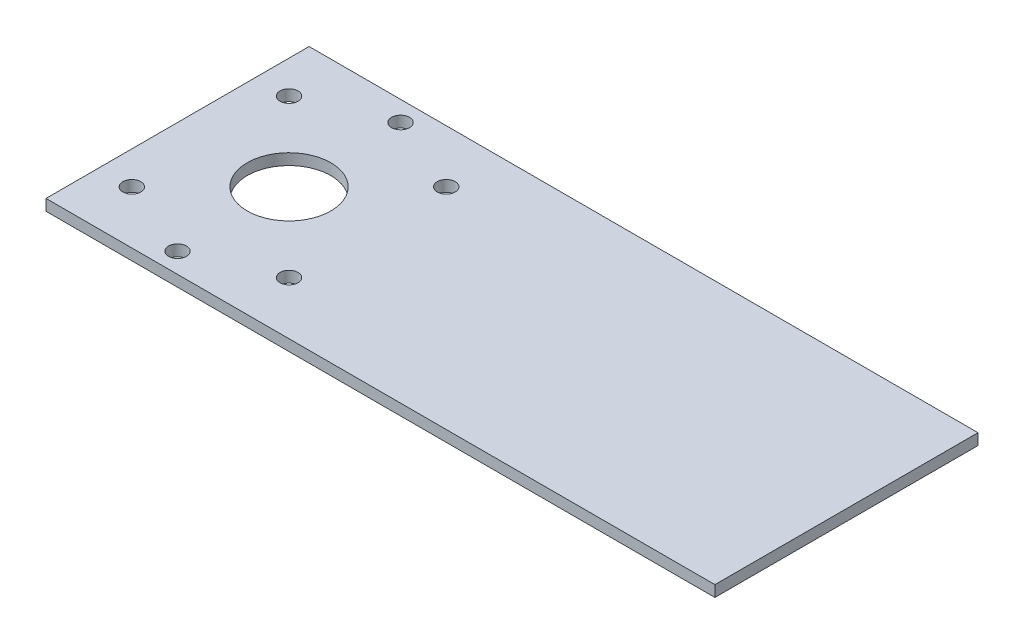
SolidWorks part; units mm, degrees
ref_plane "Front Plane" through (0, 0, 0) normal (0, 0, 1) x (1, 0, 0)
ref_plane "Top Plane" through (0, 0, 0) normal (0, 1, 0) x (1, 0, 0)
ref_plane "Right Plane" through (0, 0, 0) normal (1, 0, 0) x (0, 0, -1)
sketch "Sketch1" plane through (0, 0, 0) normal (0, 1, 0) x (1, 0, 0)
  line L0 (-101.6, 59.944) -> (-101.6, 0) construction
  line L1 (-152.4, 59.944) -> (0, 59.944)
  line L2 (-152.4, 59.944) -> (-152.4, 0)
  line L3 (-152.4, 0) -> (0, 0)
  line L4 (0, 59.944) -> (0, 0)
  dimension "D1" = 152.4
  dimension "D2" = 59.944
  dimension "D3" = 50.8
extrude "Boss-Extrude1" add sketch "Sketch1" along normal blind 2.54
sketch "Sketch4" plane through (0, 2.54, 0) normal (0, 1, 0) x (1, 0, 0)
  line L0 (-101.6, 59.944) -> (-101.6, 0) construction
  line L1 (0, 59.944) -> (-152.4, 59.944) construction
  line L2 (-152.4, 0) -> (0, 0) construction
  line L3 (-152.4, 59.944) -> (-152.4, 0) construction
  line L4 (-101.6, 0) -> (-152.4, 0) construction
  line L5 (-144.907, 47.879) -> (-109.093, 47.879) construction
  line L6 (-144.907, 47.879) -> (-144.907, 12.065) construction
  line L7 (-144.907, 12.065) -> (-109.093, 12.065) construction
  line L8 (-109.093, 47.879) -> (-109.093, 12.065) construction
  line L9 (-127, 55.372) -> (-127, 4.572) construction
  point P14 (-127, 12.065)
  point P15 (-127, 0)
  point P16 (-109.093, 29.972)
  point P17 (-101.6, 29.972)
  point P21 (-144.907, 29.972)
  point P23 (-127, 29.972)
  dimension "D1" = 50.8
  dimension "D2" = 35.814
  dimension "D3" = 50.8
sketch "Sketch7" plane through (0, 2.54, 0) normal (0, 1, 0) x (1, 0, 0)
  point P0 (-144.907, 47.879)
  point P3 (-127, 55.372)
  point P6 (-109.093, 47.879)
  point P9 (-109.093, 12.065)
  point P12 (-127, 4.572)
  point P15 (-144.907, 12.065)
hole_wizard "#97 (0.161) Diameter Hole1" positions "Sketch7" profile "Sketch6" hole size "#97" standard "ANSI Inch" end condition through all
sketch "Sketch6" plane through (-144.907, 2.54, -47.879) normal (1, 0, 0) x (0, 0, 1)
  line L0 (0, 0) -> (0, 2.54)
  line L1 (0, 2.54) -> (2.0447, 2.54)
  line L2 (2.0447, 2.54) -> (2.0447, 0)
  line L5 (2.0447, 0) -> (0, 0)
  line L11 (0, -6.35) -> (0, 107.95) construction
  dimension "Thru Hole Dia." = 4.0894
  dimension "Thru Hole Depth" = 2.54
sketch "Sketch10" plane through (0, 2.54, 0) normal (0, 1, 0) x (1, 0, 0)
  point P0 (-127, 29.972)
hole_wizard "#97 (0.75) Diameter Hole1" positions "Sketch10" profile "Sketch9" hole size "#97" standard "ANSI Inch" end condition through all
sketch "Sketch9" plane through (-127, 2.54, -29.972) normal (1, 0, 0) x (0, 0, 1)
  line L0 (0, 0) -> (0, 2.54)
  line L1 (0, 2.54) -> (9.525, 2.54)
  line L2 (9.525, 2.54) -> (9.525, 0)
  line L5 (9.525, 0) -> (0, 0)
  line L11 (0, -6.35) -> (0, 107.95) construction
  dimension "Thru Hole Dia." = 19.05
  dimension "Thru Hole Depth" = 2.54
